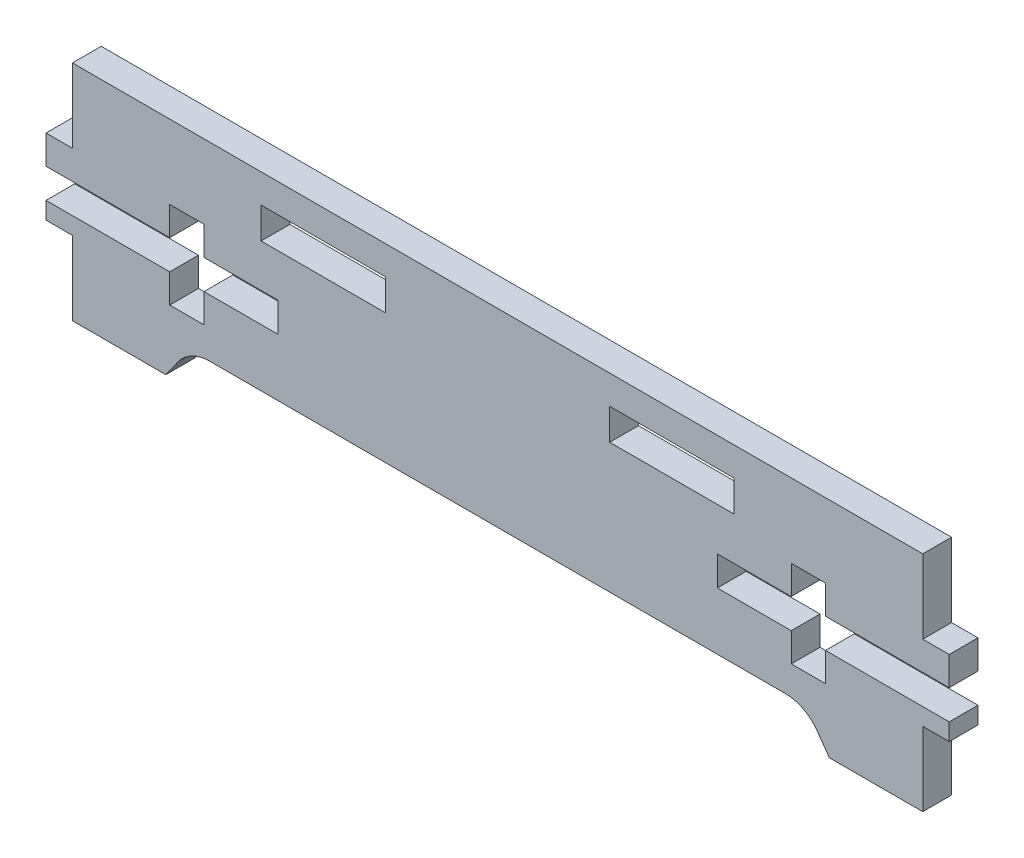
SolidWorks part; units mm, degrees
ref_plane "Front Plane" through (0, 0, 0) normal (0, 0, 1) x (1, 0, 0)
ref_plane "Top Plane" through (0, 0, 0) normal (0, 1, 0) x (1, 0, 0)
ref_plane "Right Plane" through (0, 0, 0) normal (1, 0, 0) x (0, 0, -1)
sketch "Sketch2" plane through (0, 0, 0) normal (0, 0, 1) x (1, 0, 0)
  line L0 (0, 38.7195) -> (0, -42.6567) construction
  line L1 (-54.64, 19.61) -> (54.64, 19.61)
  line L2 (54.64, 19.61) -> (54.64, 10.11)
  line L3 (54.64, 10.11) -> (58.04, 10.11)
  line L4 (58.04, 2.61) -> (58.04, 0.41)
  line L5 (58.04, 2.61) -> (42.14, 2.61)
  line L6 (58.04, 10.11) -> (58.04, 6.41)
  line L7 (42.14, 10.11) -> (37.74, 10.11)
  line L8 (42.14, 10.11) -> (42.14, 6.41)
  line L9 (37.74, 6.41) -> (28.24, 6.41)
  line L10 (0, 4.51) -> (75.8333, 4.51) construction
  line L11 (37.74, 2.61) -> (28.24, 2.61)
  line L12 (37.74, 2.61) -> (37.74, -1.09)
  line L13 (42.14, -1.09) -> (37.74, -1.09)
  line L14 (37.74, 6.41) -> (37.74, 10.11)
  line L15 (58.04, 6.41) -> (42.14, 6.41)
  line L16 (42.14, 2.61) -> (42.14, -1.09)
  line L17 (58.04, 0.41) -> (54.64, 0.41)
  line L18 (54.64, 0.41) -> (54.64, -9.09)
  line L19 (54.64, -9.09) -> (42.64, -9.09)
  line L20 (42.64, -9.09) -> (39.5723, -4.7693)
  line L21 (39.5723, -4.7693) -> (-39.5723, -4.7693)
  line L22 (28.24, 6.41) -> (28.24, 2.61)
  line L23 (-42.64, -9.09) -> (-39.5723, -4.7693)
  line L24 (-54.64, -9.09) -> (-42.64, -9.09)
  line L25 (-54.64, 0.41) -> (-54.64, -9.09)
  line L26 (-58.04, 0.41) -> (-54.64, 0.41)
  line L27 (-58.04, 2.61) -> (-58.04, 0.41)
  line L28 (-58.04, 2.61) -> (-42.14, 2.61)
  line L29 (-42.14, 2.61) -> (-42.14, -1.09)
  line L30 (-42.14, -1.09) -> (-37.74, -1.09)
  line L31 (-37.74, 2.61) -> (-37.74, -1.09)
  line L32 (-37.74, 2.61) -> (-28.24, 2.61)
  line L33 (-28.24, 6.41) -> (-28.24, 2.61)
  line L34 (-37.74, 6.41) -> (-28.24, 6.41)
  line L35 (-37.74, 6.41) -> (-37.74, 10.11)
  line L36 (-42.14, 10.11) -> (-37.74, 10.11)
  line L37 (-42.14, 10.11) -> (-42.14, 6.41)
  line L38 (-58.04, 6.41) -> (-42.14, 6.41)
  line L39 (-58.04, 10.11) -> (-58.04, 6.41)
  line L40 (-54.64, 10.11) -> (-58.04, 10.11)
  line L41 (-54.64, 19.61) -> (-54.64, 10.11)
  point P29 (0, -4.7693)
  point P47 (0, 19.61)
  dimension "D1" = 54.64
  dimension "D2" = 9.5
  dimension "D3" = 3.7
  dimension "D4" = 15.9
  dimension "D5" = 3.7
  dimension "D6" = 9.5
  dimension "D7" = 4.4
  dimension "D8" = 6
  dimension "D9" = 3.4
  dimension "D10" = 9.5
  dimension "D11" = 3.8
  dimension "D12" = 12
  dimension "D13" = 3.4
extrude "Boss-Extrude1" add sketch "Sketch2" along normal blind 3.7
fillet "Fillet1" radius 5 2 edges at (39.5723, -4.7693, 1.85) (-39.5723, -4.7693, 1.85)
sketch "Sketch3" plane through (0, 0, 3.7) normal (0, 0, 1) x (1, 0, 0)
  line L0 (0, 19.61) -> (0, -9.4252) construction
  line L1 (54.64, 19.61) -> (-54.64, 19.61) construction
  line L2 (54.64, 10.11) -> (54.64, 19.61) construction
  line L3 (30.4, 11.91) -> (14.4, 11.91)
  line L4 (30.4, 11.91) -> (30.4, 15.91)
  line L5 (30.4, 15.91) -> (14.4, 15.91)
  line L6 (14.4, 11.91) -> (14.4, 15.91)
  line L7 (30.4, 11.91) -> (14.4, 15.91) construction
  line L8 (30.4, 15.91) -> (14.4, 11.91) construction
  line L9 (-30.4, 15.91) -> (-14.4, 15.91)
  line L10 (-14.4, 11.91) -> (-14.4, 15.91)
  line L11 (-30.4, 11.91) -> (-14.4, 11.91)
  line L12 (-30.4, 11.91) -> (-30.4, 15.91)
  point P5 (22.4, 13.91)
  dimension "D1" = 24.24
  dimension "D2" = 3.7
  dimension "D3" = 4
  dimension "D4" = 16
extrude "Cut-Extrude1" cut sketch "Sketch3" against normal through all
